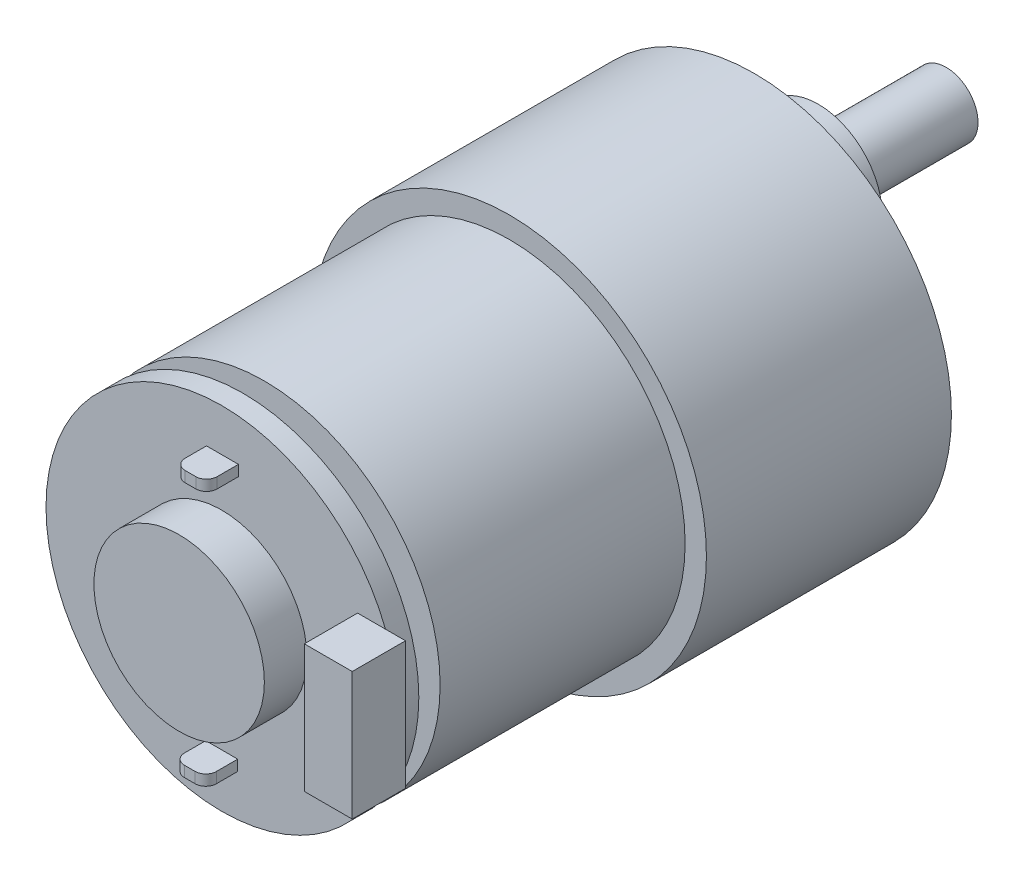
SolidWorks part; units mm, degrees
ref_plane "前视基准面" through (0, 0, 0) normal (0, 0, 1) x (1, 0, 0)
ref_plane "上视基准面" through (0, 0, 0) normal (0, 1, 0) x (1, 0, 0)
ref_plane "右视基准面" through (0, 0, 0) normal (1, 0, 0) x (0, 0, -1)
sketch "草图1" plane through (0, 0, 0) normal (0, 0, 1) x (1, 0, 0)
  circle A0 centre (0, 0) radius 18.5
extrude "凸台-拉伸3" add sketch "草图1" along normal blind 23 contours A0
sketch "草图3" plane through (0, 0, 23) normal (0, 0, 1) x (1, 0, 0)
  circle A0 centre (0, 0) radius 16.5
extrude "凸台-拉伸4" add sketch "草图3" along normal blind 23
sketch "草图4" plane through (0, 0, 0) normal (0, 0, -1) x (-1, 0, 0)
  circle A0 centre (0, 7) radius 6
  dimension "D1" = 7
extrude "凸台-拉伸5" add sketch "草图4" along normal blind 6 contours A0
sketch "草图6" plane through (0, 0, -6) normal (0, 0, -1) x (-1, 0, 0)
  circle A0 centre (0, 7) radius 3
extrude "凸台-拉伸6" add sketch "草图6" along normal blind 12
sketch "草图7" plane through (0, 0, 46) normal (0, 0, 1) x (1, 0, 0)
  circle A0 centre (0, 0) radius 2
extrude "凸台-拉伸7" add sketch "草图7" along normal blind 2
sketch "草图8" plane through (0, 0, 46) normal (0, 0, 1) x (1, 0, 0)
  line L0 (-1.5, -11.5) -> (1.5, -11.5)
  line L1 (-1.4335, 12.5) -> (1.5665, 12.5)
  line L2 (-1.4335, 12.5) -> (-1.4335, 11.5)
  line L3 (-1.4335, 11.5) -> (1.5665, 11.5)
  line L4 (1.5665, 12.5) -> (1.5665, 11.5)
  line L5 (-1.4335, 12.5) -> (1.5665, 11.5) construction
  line L6 (-1.4335, 11.5) -> (1.5665, 12.5) construction
  line L7 (-1.5, -11.5) -> (-1.5, -12.5)
  line L8 (-1.5, -12.5) -> (1.5, -12.5)
  line L9 (1.5, -11.5) -> (1.5, -12.5)
  line L10 (-1.5, -11.5) -> (1.5, -12.5) construction
  line L11 (-1.5, -12.5) -> (1.5, -11.5) construction
  point P0 (0.0665, 12)
  point P5 (0, -12)
  dimension "D1" = 3
  dimension "D2" = 1
  dimension "D3" = 12
  dimension "D4" = 12
extrude "凸台-拉伸8" add sketch "草图8" along normal blind 7
sketch "草图9" plane through (0, 0, 48) normal (0, 0, 1) x (1, 0, 0)
  circle A0 centre (0, 0) radius 16.5
extrude "凸台-拉伸9" add sketch "草图9" along normal blind 2
sketch "草图10" plane through (0, 0, 50) normal (0, 0, 1) x (1, 0, 0)
  line L1 (12.75, 6) -> (17.25, 6)
  line L2 (12.75, 6) -> (12.75, -6)
  line L3 (12.75, -6) -> (17.25, -6)
  line L4 (17.25, 6) -> (17.25, -6)
  line L5 (12.75, 6) -> (17.25, -6) construction
  line L6 (12.75, -6) -> (17.25, 6) construction
  point P0 (15, 0)
  dimension "D1" = 15
  dimension "D2" = 4.5
  dimension "D3" = 12
extrude "凸台-拉伸10" add sketch "草图10" along normal blind 5
fillet "圆角1" radius 1 4 edges at (-1.5, -12, 53) (1.5, -12, 53) (-1.4335, 12, 53) (1.5665, 12, 53)
sketch "草图11" plane through (0, 0, 50) normal (0, 0, 1) x (1, 0, 0)
  circle A0 centre (0, 0) radius 8
extrude "凸台-拉伸11" add sketch "草图11" along normal blind 4
